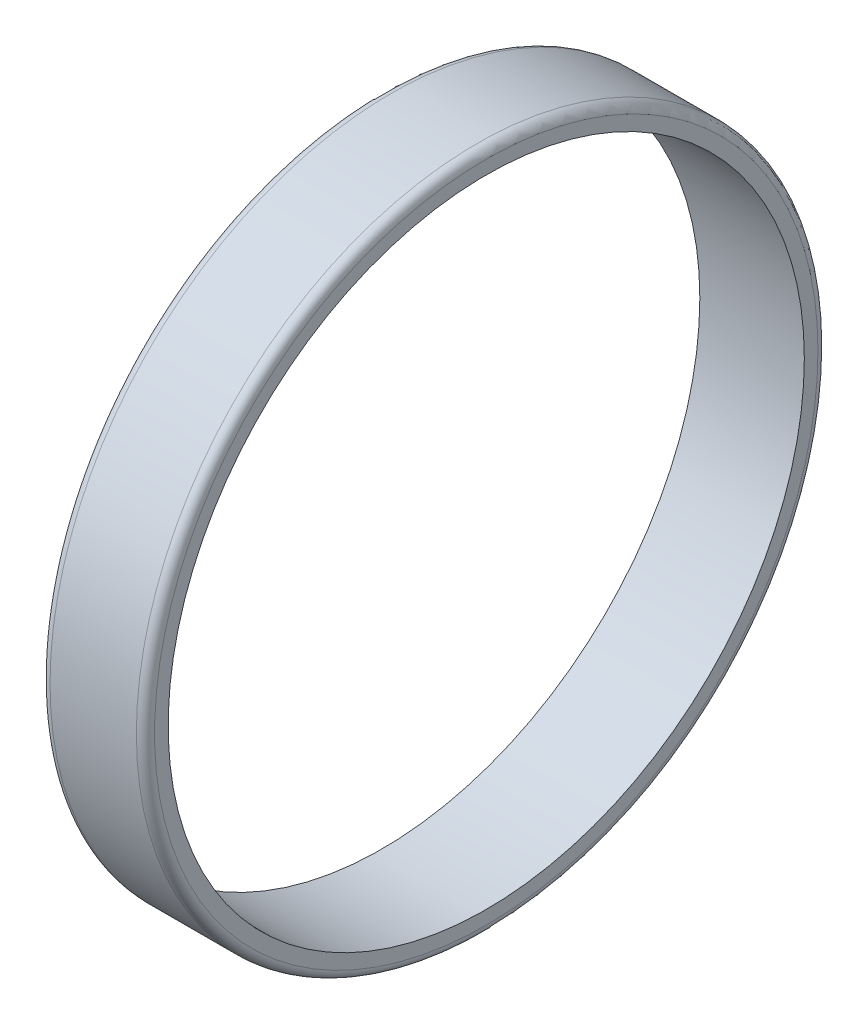
SolidWorks part; units mm, degrees
material "Резина"
ref_plane "Спереди" through (0, 0, 0) normal (0, 0, 1) x (1, 0, 0)
ref_plane "Сверху" through (0, 0, 0) normal (0, 1, 0) x (1, 0, 0)
ref_plane "Справа" through (0, 0, 0) normal (1, 0, 0) x (0, 0, -1)
sketch "Эскиз1" plane through (0, 0, 0) normal (1, 0, 0) x (0, 0, -1)
  circle A0 centre (0, 0) radius 37.5
  circle A1 centre (0, 0) radius 35
  dimension "D1" = 2.5
  dimension "D2" = 70
extrude "Бобышка-Вытянуть1" add sketch "Эскиз1" along normal blind 11.5
fillet "Скругление1" radius 1 2 edges at (0, 0, -37.5) (11.5, 0, -37.5)
